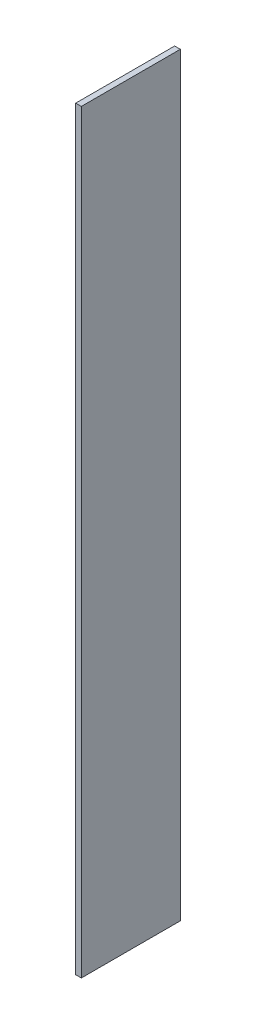
SolidWorks part; units mm, degrees
ref_plane "Спереди" through (0, 0, 0) normal (0, 0, 1) x (1, 0, 0)
ref_plane "Сверху" through (0, 0, 0) normal (0, 1, 0) x (1, 0, 0)
ref_plane "Справа" through (0, 0, 0) normal (1, 0, 0) x (0, 0, -1)
sketch "Эскиз1" plane through (0, 0, 0) normal (0, 1, 0) x (1, 0, 0)
  line L1 (1, 10.1482) -> (5, 10.1482)
  line L2 (1, 10.1482) -> (1, -59.7541)
  line L3 (1, -59.7541) -> (5, -59.7541)
  line L4 (5, 10.1482) -> (5, -59.7541)
  dimension "D1" = 4
extrude "Вытянуть1" add sketch "Эскиз1" along normal up to surface (533.2137 mm away)
